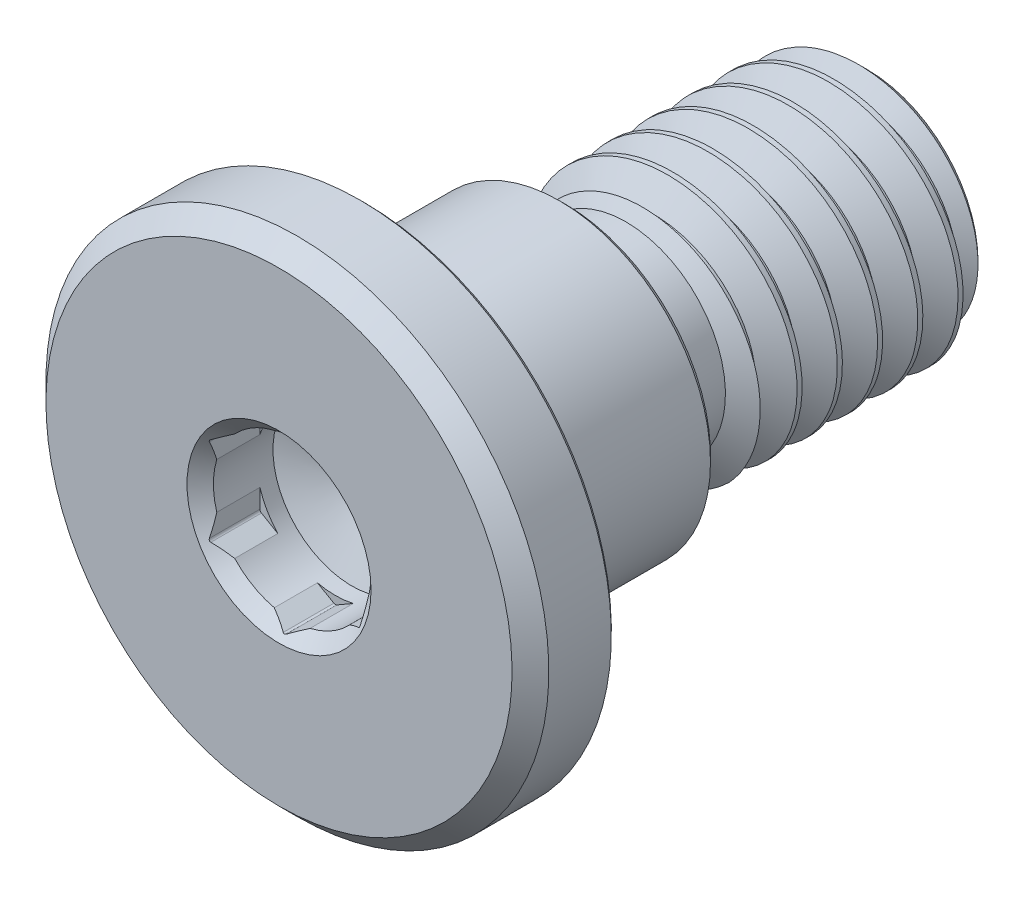
SolidWorks part; units mm, degrees
ref_plane "Front Plane" through (0, 0, 0) normal (0, 0, 1) x (1, 0, 0)
ref_plane "Top Plane" through (0, 0, 0) normal (0, 1, 0) x (1, 0, 0)
ref_plane "Right Plane" through (0, 0, 0) normal (1, 0, 0) x (0, 0, -1)
sketch "Sketch1" plane through (0, 0, 0) normal (1, 0, 0) x (0, 0, -1)
  line L0 (10, 0) -> (0, 0) construction
  line L1 (0, 0) -> (-1.7, 0) construction
  line L2 (-1.7, 5) -> (-1.7, -5) construction
  line L3 (0, 5) -> (0, -5) construction
  line L4 (4, 2.5) -> (10, 2.5) construction
  line L5 (9.95, 2.5866) -> (10.75, 2.5866) construction
  line L6 (10.75, 2.5866) -> (10.35, 1.8938) construction
  line L7 (10.35, 1.8938) -> (9.95, 2.5866) construction
  line L8 (10, 2.5) -> (10.7, 2.5) construction
  line L9 (10.3, 1.9804) -> (10.4, 1.9804) construction
  line L10 (10.35, 1.8938) -> (10.35, 1.9804) construction
  line L11 (10.35, 2.5) -> (10.35, 2.5866) construction
  line L12 (-1.7, 1.5) -> (-0.2525, 1.5) construction
  line L13 (-0.2525, 1.5) -> (-0.2525, -1.5) construction
  line L14 (-0.2525, -1.5) -> (-1.7, -1.5) construction
  line L15 (4, 3) -> (4, -3) construction
  line L16 (-1.7, 5) -> (0, 5) construction
  line L17 (4, -2.5) -> (10, -2.5) construction
  point P12 (-0.2525, 0)
  point P27 (4, 0)
  point P36 (8.8, -2.5)
  dimension "Screw Size Decimal Equivalent" = 5
  dimension "Thread Length" = 6
  dimension "Shoulder Diameter" = 6
  dimension "Head Height" = 1.7
  dimension "Head Diameter" = 10
  dimension "Drive Size" = 3
  dimension "Thread Pitch" = 0.8
  dimension "Pitch/8" = 0.1
  dimension "Thread Note" = 1.2
  dimension "Shoulder Length" = 4
  dimension "Approximate Drive Depth" = 1.4475
sketch "Sketch2" plane through (0, 0, 0) normal (1, 0, 0) x (0, 0, -1)
  line L0 (-1.7, 5) -> (0, 5)
  line L1 (0, 5) -> (0, 3)
  line L2 (0, 3) -> (4, 3)
  line L3 (4, 3) -> (4, 2.5)
  line L4 (4, 2.5) -> (10, 2.5)
  line L5 (10, 2.5) -> (10, 0)
  line L6 (10, 0) -> (-1.7, 0)
  line L7 (-1.7, 0) -> (-1.7, 5)
revolve "Revolve1" add sketch "Sketch2" angle 360 about L1
chamfer "Chamfer1" distance 0.3655 angle 45 1 edges at (0, 5, 1.7)
chamfer "Chamfer4" distance 0.0914 angle 45 1 edges at (0, 5, 0)
sketch "Sketch3" plane through (0, 0, 0) normal (1, 0, 0) x (0, 0, -1)
  line L0 (0, 3) -> (0.6374, 3)
  line L1 (4, 3) -> (0, 3) construction
  line L2 (0.6374, 3) -> (0.4507, 2.8133)
  line L3 (0, 5) -> (0, -5) construction
  line L4 (0, 2.736) -> (0.264, 2.736) construction
  arc A0 (0.4507, 2.8133) -> (0, 3) centre (0.264, 3) cw
  dimension "D2" = 0.264
  dimension "D1" = 45
revolve "Cut-Revolve1" cut sketch "Sketch3" angle 360 about L0
sketch "Sketch4" plane through (0, 0, 0) normal (1, 0, 0) x (0, 0, -1)
  line L0 (4, 2.5) -> (10, 2.5) construction
  line L1 (4, 2.5) -> (5.5015, 2.5)
  line L2 (4, 2.5) -> (4, 1.9778)
  line L3 (4, 1.9778) -> (5.2, 1.9778)
  line L4 (5.5015, 2.5) -> (5.2, 1.9778)
  line L5 (4, 3) -> (4, -3) construction
  line L7 (10.3, 1.9804) -> (10.4, 1.9804) construction
  point P8 (5.2015, 1.9804)
  dimension "D1" = 1.2
  dimension "D2" = 60
  dimension "D3" = 0.0025
revolve "Cut-Revolve2" cut sketch "Sketch4" angle 360 about L0
chamfer "Chamfer2" distance 0.12 angle 45 1 edges at (0, 3, -4)
fillet "Fillet1" radius 0.096 1 edges at (0, 1.9778, -4)
chamfer "Chamfer3" distance 0.3 angle 45 1 edges at (0, 2.5, -10)
sketch "Sketch11" plane through (0, 0, 1.7) normal (0, 0, 1) x (1, 0, 0)
  circle A0 centre (0, 0) radius 1.5675
  dimension "D1" = 3.135
extrude "Cut-Extrude4" cut sketch "Sketch11" against normal up to vertex (1.4475 mm away) up to point (0, 1.5, 0.2525)
sketch "Sketch5" plane through (0, 0, 1.7) normal (0, 0, 1) x (1, 0, 0)
  line L1 (0, 1.7321) -> (-1.5, 0.866)
  line L2 (-1.5, 0.866) -> (-1.5, -0.866)
  line L3 (-1.5, -0.866) -> (0, -1.7321)
  line L4 (0, -1.7321) -> (1.5, -0.866)
  line L5 (1.5, -0.866) -> (1.5, 0.866)
  line L6 (1.5, 0.866) -> (0, 1.7321)
  circle A0 centre (0, 0) radius 1.5 construction
  circle A1 centre (0, 0) radius 5 construction
extrude "Cut-Extrude1" cut sketch "Sketch5" against normal blind 1.1204
sketch "Sketch6" plane through (0, 0, 1.7) normal (0, 0, 1) x (1, 0, 0)
  circle A0 centre (0, 0) radius 1.83
  dimension "D1" = 3.66
extrude "Cut-Extrude2" cut sketch "Sketch6" against normal up to vertex (1.4475 mm away) draft 45 up to point (0, 1.5, 0.2525)
sketch "Sketch9" plane through (0, 0, 0.2525) normal (0, 0, 1) x (1, 0, 0)
  circle A0 centre (0, 0) radius 1.5675
  circle A2 centre (0, 0) radius 1.5675 construction
extrude "Cut-Extrude3" cut sketch "Sketch9" against normal through all draft 70
fillet "Fillet2" radius 0.06 6 edges at (1.5, 0.866, 1.0908) (0, 1.7321, 1.0908) (-1.5, 0.866, 1.0908) (0, -1.7321, 1.0908) (1.5, -0.866, 1.0908) (-1.5, -0.866, 1.0908)
fillet "Fillet3" radius 0.3749 1 edges at (0, 3, -0.6374)
ref_plane "Plane1" through (0, 0, -5.2) normal (0, 0, 1) x (1, 0, 0)
split "Split1" trim tools "Plane1" bodies to split 113 resulting bodies 109 110
sketch "Sketch7" plane through (0, 0, 0) normal (1, 0, 0) x (0, 0, -1)
  line L0 (10.3, 1.9804) -> (10.4, 1.9804)
  line L1 (10.4, 1.9804) -> (10.725, 2.5433)
  line L2 (10.75, 2.5866) -> (10.35, 1.8938) construction
  line L3 (10.725, 2.5433) -> (9.975, 2.5433)
  line L4 (10.35, 1.8938) -> (9.95, 2.5866) construction
  line L5 (9.975, 2.5433) -> (10.3, 1.9804)
  line L6 (10.35, 2.5) -> (10.35, 2.5866) construction
  point P12 (10.35, 2.5433)
sketch "Sketch8" plane through (0, 0, -10) normal (0, 0, -1) x (-1, 0, 0)
  circle A0 centre (0, 0) radius 2.5
curve "Helix/Spiral1" pitch 0.8 height 5.6 turns 7
sweep "Cut-Sweep1" cut profiles "Sketch7" path "Helix/Spiral1"
ref_plane "Plane2" through (0, 0, -5.2015) normal (0, 0, 1) x (1, 0, 0)
sketch "Sketch10" plane through (0, 0, -5.2015) normal (0, 0, 1) x (1, 0, 0)
  circle A0 centre (0, 0) radius 1.9804
extrude "Boss-Extrude1" add sketch "Sketch10" along normal through all draft 60
equation "\"Pitch/8@Sketch1\" = \"Thread Pitch@Sketch1\" / 8"
equation "\"Thread Note@Sketch1\"=\"Thread Pitch@Sketch1\"*1.5"
equation "\"D1@Chamfer1\"=\"Head Height@Sketch1\"*.215"
equation "\"D1@Sketch4\"=\"Thread Pitch@Sketch1\"*1.5"
equation "\"D1@Chamfer2\"=\"Shoulder Diameter@Sketch1\"*.02"
equation "\"D1@Fillet1\" = \"D1@Chamfer2\" * .8"
equation "\"D1@Chamfer3\"=\"Thread Pitch@Sketch1\" * .375"
equation "\"D1@Sketch6\"=\"Drive Size@Sketch1\" * 1.22"
equation "\"D1@Fillet2\"=\"Drive Size@Sketch1\"*.02"
equation "\"D4@Helix/Spiral1\"=\"Thread Pitch@Sketch1\""
equation "\"D3@Helix/Spiral1\"=\"Thread Length@Sketch1\" - \"Thread Pitch@Sketch1\"*.5"
equation "\"Approximate Drive Depth@Sketch1\"=\"Drive Size@Sketch1\"*.4825"
equation "\"D1@Chamfer4\"=\"D1@Chamfer1\"*.25"
equation "\"D2@Sketch3\"=\"Shoulder Diameter@Sketch1\"*.044"
equation "\"D1@Fillet3\"=\"D2@Sketch3\" * 1.42"
equation "\"D1@Sketch11\"=\"Drive Size@Sketch1\"*1.045"
equation "\"D1@Cut-Extrude1\"=\"Approximate Drive Depth@sketch1\"*.774"
